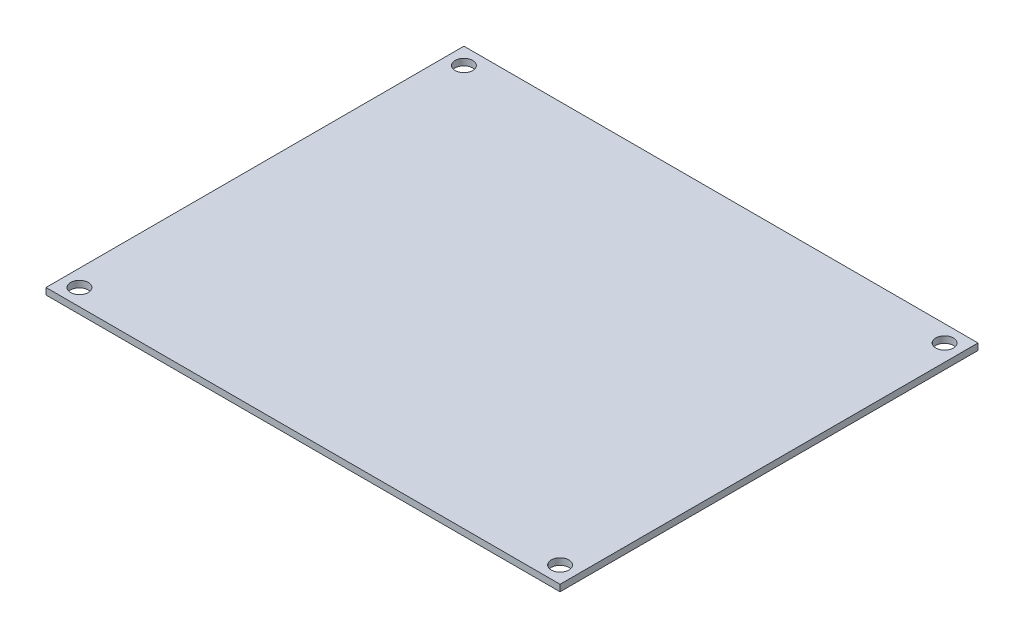
SolidWorks part; units mm, degrees
ref_plane "Front" through (0, 0, 0) normal (0, 0, 1) x (1, 0, 0)
ref_plane "Top" through (0, 0, 0) normal (0, 1, 0) x (1, 0, 0)
ref_plane "Right" through (0, 0, 0) normal (1, 0, 0) x (0, 0, -1)
sketch "Sketch1" plane through (0, 0, 0) normal (0, 1, 0) x (1, 0, 0)
  line L0 (0, 100) -> (123, 0) construction
  line L1 (0, 0) -> (123, 0)
  line L2 (0, 0) -> (0, 100)
  line L3 (0, 100) -> (123, 100)
  line L4 (123, 0) -> (123, 100)
  line L5 (123, 100) -> (0, 0) construction
  line L7 (4, 4) -> (119, 4) construction
  line L8 (4, 4) -> (4, 96) construction
  line L9 (4, 96) -> (119, 96) construction
  line L10 (119, 4) -> (119, 96) construction
  line L11 (4, 4) -> (119, 96) construction
  line L12 (4, 96) -> (119, 4) construction
  circle A1 centre (4, 96) radius 2.1
  circle A2 centre (119, 96) radius 2.1
  circle A3 centre (119, 4) radius 2.1
  circle A4 centre (4, 4) radius 2.1
  point P4 (61.5, 50)
  dimension "D3" = 92
  dimension "D6" = 4.2
  dimension "D1" = 123
  dimension "D2" = 100
  dimension "D4" = 115
extrude "Boss-Extrude1" add sketch "Sketch1" along normal blind 1.57
